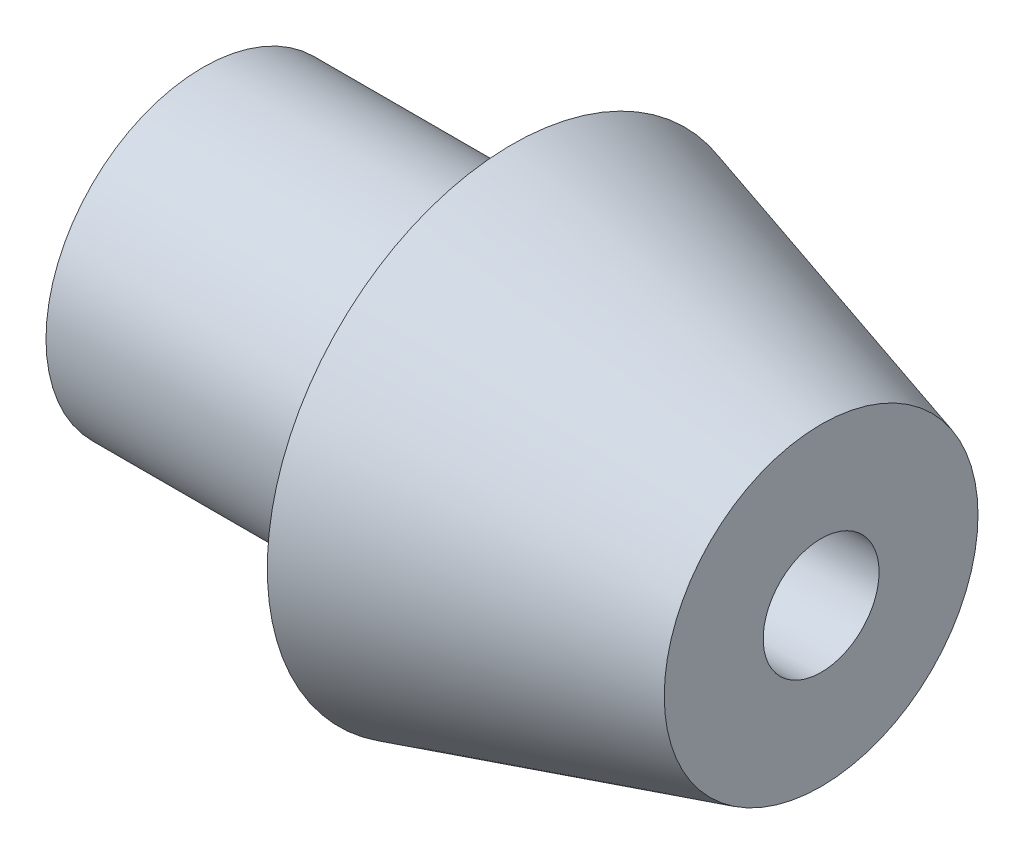
SolidWorks part; units mm, degrees
ref_plane "Front Plane" through (0, 0, 0) normal (0, 0, 1) x (1, 0, 0)
ref_plane "Top Plane" through (0, 0, 0) normal (0, 1, 0) x (1, 0, 0)
ref_plane "Right Plane" through (0, 0, 0) normal (1, 0, 0) x (0, 0, -1)
sketch "Sketch4" plane through (0, 0, 0) normal (0, 0, 1) x (1, 0, 0)
  line L1 (-8.5939, 0) -> (-8.5939, 4.75)
  line L2 (-8.5939, 4.75) -> (-2.5939, 3.0449)
  line L3 (-2.5939, 3.0449) -> (-2.5939, 0)
  line L4 (0, 0) -> (-13.2727, 0) construction
  line L5 (-8.5939, 0) -> (-2.5939, 0)
  dimension "D1" = 4
  dimension "D2" = 4.75
  dimension "D3" = 6
revolve "Barb" add sketch "Sketch4" angle 360 about L4
sketch "Sketch5" plane through (-2.5939, 0, 0) normal (1, 0, 0) x (0, 0, -1)
  circle A0 centre (0, 0) radius 1.125
  dimension "D1" = 2.25
extrude "Lumen" cut sketch "Sketch5" against normal up to next
sketch "Sketch6" plane through (-8.5939, 0, 0) normal (-1, 0, 0) x (0, 0, 1)
  circle A0 centre (0, 0) radius 1.125 construction
  circle A1 centre (0, 0) radius 1.125
  circle A2 centre (0, 0) radius 3.0449 construction
  circle A3 centre (0, 0) radius 3.0449
extrude "MinChannel" add sketch "Sketch6" along normal blind 6
fillet "BarbChannelFillet" radius 1 1 edges at (-8.5939, 0, 3.0449)
equation "\"channel_diameter\" = 4mm"
equation "\"channel_length\" = 12mm"
equation "\"barb_large_diameter\"= 4.75mm"
equation "\"barb_length\"= 6mm"
equation "\"D1@Sketch4\"=\"channel_diameter\""
equation "\"D2@Sketch4\"=\"barb_large_diameter\""
equation "\"D3@Sketch4\"=\"barb_length\""
equation "\"lumen_diameter\"= 2.25mm"
equation "\"D1@Sketch5\"=\"lumen_diameter\""
equation "\"D1@MinChannel\" = \"barb_length\""
